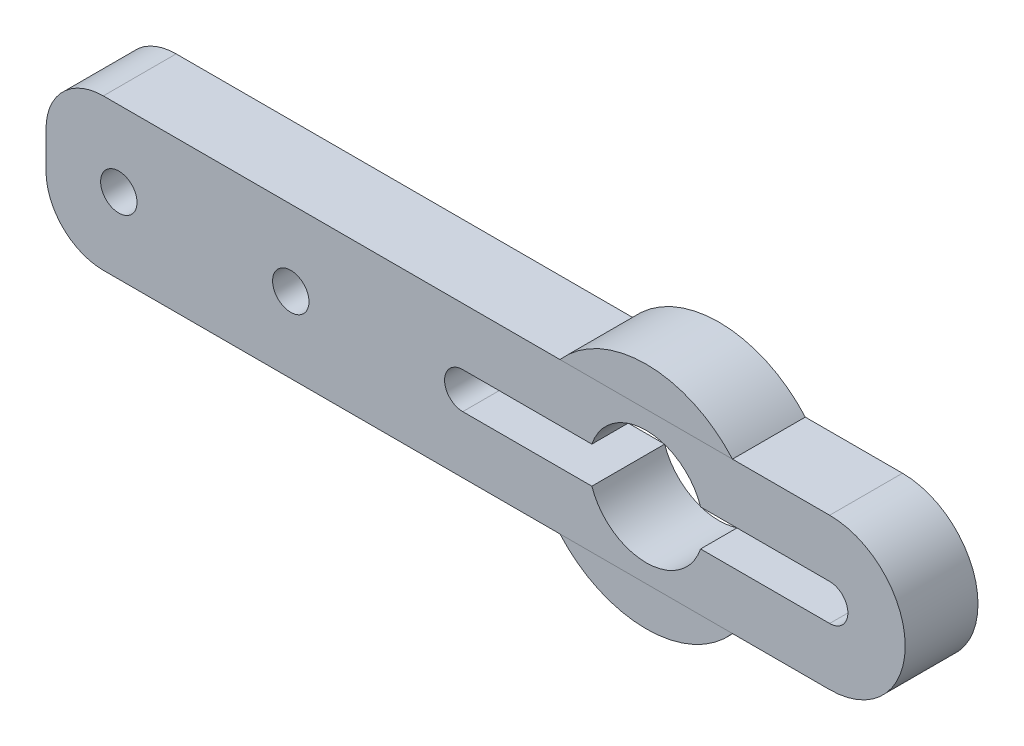
SolidWorks part; units mm, degrees
ref_plane "Front" through (0, 0, 0) normal (0, 0, 1) x (1, 0, 0)
ref_plane "Top" through (0, 0, 0) normal (0, 1, 0) x (1, 0, 0)
ref_plane "Right" through (0, 0, 0) normal (1, 0, 0) x (0, 0, -1)
sketch "Sketch1" plane through (0, 0, 0) normal (0, 0, 1) x (1, 0, 0)
  line L0 (0, 0) -> (32, 0) construction
  line L1 (0, 1.5875) -> (32, 1.5875)
  line L2 (0, -1.5875) -> (32, -1.5875)
  line L3 (0, 6.5875) -> (32, 6.5875)
  line L4 (0, -6.5875) -> (32, -6.5875)
  arc A0 (0, 1.5875) -> (0, -1.5875) centre (0, 0) ccw
  arc A1 (32, -1.5875) -> (32, 1.5875) centre (32, 0) ccw
  arc A2 (32, -6.5875) -> (32, 6.5875) centre (32, 0) ccw
  arc A3 (0, 6.5875) -> (0, -6.5875) centre (0, 0) ccw
  point P3 (16, 0)
  dimension "D1" = 1.5875
  dimension "D2" = 32
  dimension "D3" = 5
extrude "Boss-Extrude1" add sketch "Sketch1" along normal blind 6.35
sketch "Sketch2" plane through (0, 0, 6.35) normal (0, 0, 1) x (1, 0, 0)
  line L1 (-1.5875, -6.5875) -> (-36.35, -6.5875)
  line L3 (-1.5875, 6.5875) -> (-36.35, 6.5875)
  line L4 (-36.35, -6.5875) -> (-36.35, 6.5875)
  line L5 (-1.5875, -3.7657) -> (-1.5875, 4.6219)
  line L6 (-1.5875, -3.7657) -> (1.8179, -6.5875)
  line L7 (0, -6.5875) -> (32, -6.5875) construction
  line L8 (1.8179, -6.5875) -> (-1.5875, -6.5875)
  line L9 (-1.5875, 4.6219) -> (1.3218, 5.9987)
  line L10 (1.3218, 5.9987) -> (1.8097, 6.5875)
  line L11 (32, 6.5875) -> (0, 6.5875) construction
  line L12 (1.8097, 6.5875) -> (-1.5875, 6.5875)
  circle A0 centre (-15, 0) radius 1.5875
  circle A1 centre (-30, 0) radius 1.5875
  arc A4 (0, 1.5875) -> (0, -1.5875) centre (0, 0) ccw construction
  dimension "D1" = 15
  dimension "D3" = 3.175
  dimension "D2" = 15
  dimension "D4" = 6.35
extrude "Boss-Extrude2" add sketch "Sketch2" against normal blind 6.35
fillet "Fillet1" radius 5 2 edges at (-36.35, 6.5875, 3.175) (-36.35, -6.5875, 3.175)
sketch "Sketch3" plane through (0, 0, 6.35) normal (0, 0, 1) x (1, 0, 0)
  circle A0 centre (16, 0) radius 5
  dimension "D1" = 10
extrude "Cut-Extrude1" cut sketch "Sketch3" against normal through all
sketch "Sketch4" plane through (0, 0, 6.35) normal (0, 0, 1) x (1, 0, 0)
  line L0 (24.0732, -5.9011) -> (7.9268, -5.9011)
  line L2 (7.5234, 5.3054) -> (24.4766, 5.3054)
  circle A0 centre (16, 0) radius 10
  arc A1 (11.2587, -1.5875) -> (20.7413, -1.5875) centre (16, 0) ccw construction
  line M9 (32, 6.5875) -> (-31.35, 6.5875)
  line M13 (-31.35, -6.5875) -> (32, -6.5875)
  dimension "D1" = 5
extrude "Boss-Extrude3" add sketch "Sketch4" against normal blind 6.35 separate body contours A0 M13 | A0 M9
